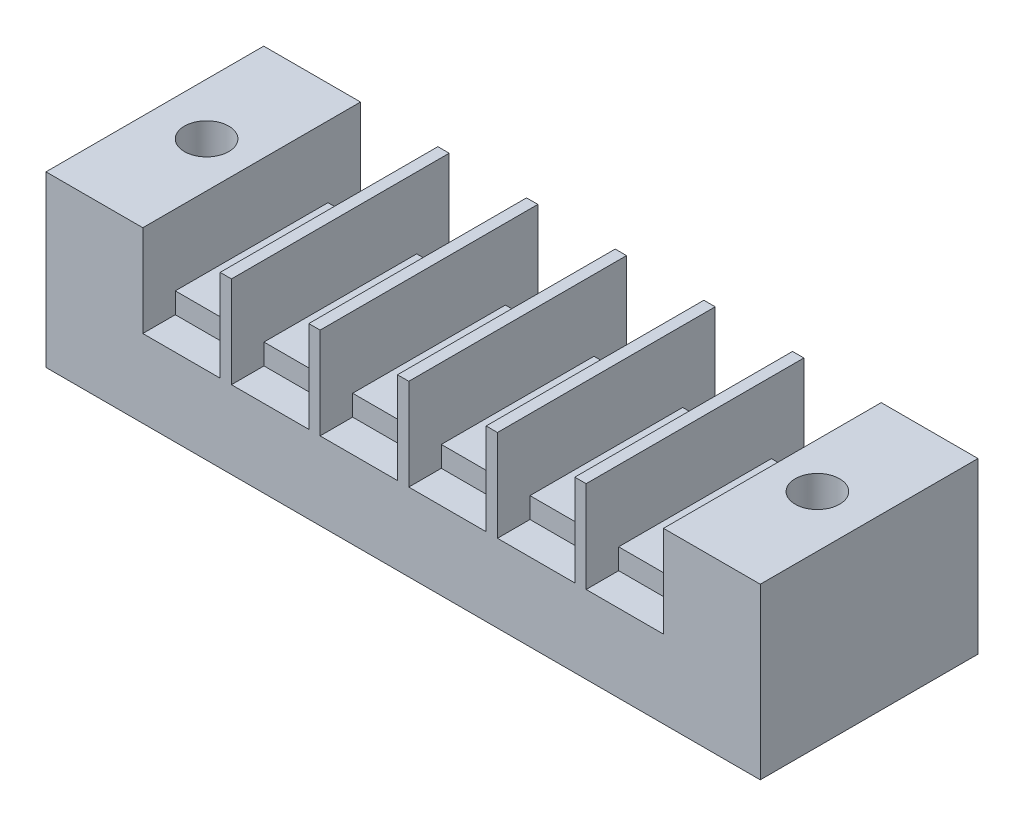
SolidWorks part; units mm, degrees
ref_plane "正面" through (0, 0, 0) normal (0, 0, 1) x (1, 0, 0)
ref_plane "平面" through (0, 0, 0) normal (0, 1, 0) x (1, 0, 0)
ref_plane "右側面" through (0, 0, 0) normal (1, 0, 0) x (0, 0, -1)
sketch "ｽｹｯﾁ1" plane through (0, 0, 0) normal (0, 1, 0) x (1, 0, 0)
  line L0 (-36.25, 0) -> (36.25, 0) construction
  line L1 (-36.25, 11.05) -> (36.25, 11.05)
  line L2 (-36.25, 11.05) -> (-36.25, -11.05)
  line L3 (-36.25, -11.05) -> (36.25, -11.05)
  line L4 (36.25, 11.05) -> (36.25, -11.05)
  line L5 (-36.25, 11.05) -> (36.25, -11.05) construction
  line L6 (-36.25, -11.05) -> (36.25, 11.05) construction
  line L7 (0, 11.05) -> (0, -11.05) construction
  circle A0 centre (31, 0) radius 2.25
  circle A1 centre (-31, 0) radius 2.25
  point P0 (0, 0)
  dimension "D3" = 4.5
  dimension "D1" = 72.5
  dimension "D2" = 22.1
  dimension "D4" = 31
extrude "ﾎﾞｽ - 押し出し1" add sketch "ｽｹｯﾁ1" along normal blind 17.2
sketch "ｽｹｯﾁ2" plane through (0, 17.2, 0) normal (0, 1, 0) x (1, 0, 0)
  line L0 (36.25, 11.05) -> (-36.25, 11.05) construction
  line L1 (18.575, 11.05) -> (26.425, 11.05)
  line L2 (18.575, 11.05) -> (18.575, -11.05)
  line L3 (18.575, -11.05) -> (26.425, -11.05)
  line L4 (26.425, 11.05) -> (26.425, -11.05)
  line L5 (-36.25, -11.05) -> (36.25, -11.05) construction
  line L6 (22.5, 11.05) -> (22.5, -11.05) construction
  line L7 (0, 11.05) -> (0, -11.05) construction
  dimension "D1" = 22.5
  dimension "D2" = 7.85
extrude "ｶｯﾄ - 押し出し1" cut sketch "ｽｹｯﾁ2" against normal blind 7.2
sketch "ｽｹｯﾁ3" plane through (0, 10, 0) normal (0, 1, 0) x (1, 0, 0)
  line L0 (26.425, -11.05) -> (26.425, 11.05) construction
  line L2 (26.425, 7.75) -> (18.575, 7.75)
  line L3 (26.425, 7.75) -> (26.425, 11.05)
  line L4 (26.425, 11.05) -> (18.575, 11.05)
  line L5 (18.575, 7.75) -> (18.575, 11.05)
  dimension "D1" = 3.3
extrude "ｶｯﾄ - 押し出し2" cut sketch "ｽｹｯﾁ3" against normal blind 2.1
sketch "ｽｹｯﾁ4" plane through (0, 10, 0) normal (0, 1, 0) x (1, 0, 0)
  line L0 (0, 0) -> (26.425, 0) construction
  line L1 (26.425, -11.05) -> (26.425, 7.75) construction
  line L2 (22.5, 7.75) -> (22.5, 0) construction
  line L3 (18.575, 7.75) -> (26.425, 7.75) construction
  circle A0 centre (22.5, 4) radius 1.75
  point P11 (0, 0)
  dimension "D1" = 3.5
  dimension "D2" = 4
extrude "ｶｯﾄ - 押し出し3" cut sketch "ｽｹｯﾁ4" against normal blind 5
mirror "ﾐﾗｰ1" about plane through (0, 0, 0) normal (0, 0, 1) of "ｶｯﾄ - 押し出し3", "ｶｯﾄ - 押し出し2"
pattern_linear "直線ﾊﾟﾀｰﾝ1" count 6 spacing 9 along (-1, 0, 0) of "ｶｯﾄ - 押し出し1", "ｶｯﾄ - 押し出し2", "ｶｯﾄ - 押し出し3", "ﾐﾗｰ1"
